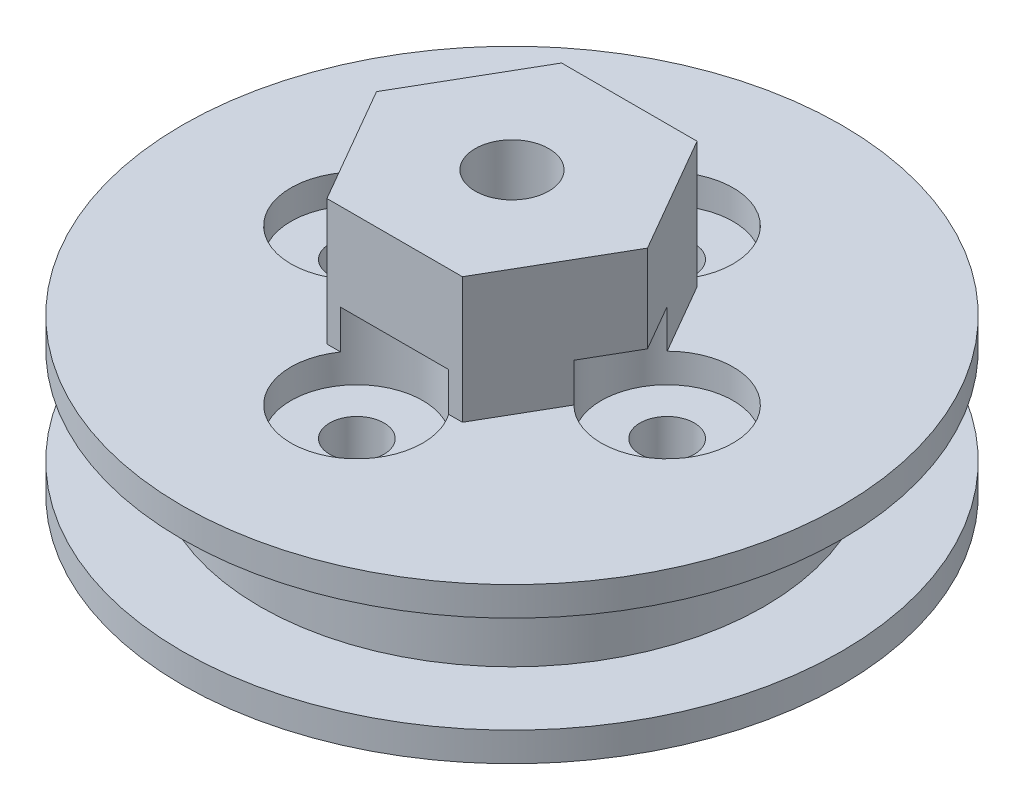
SolidWorks part; units mm, degrees
ref_plane "前视基准面" through (0, 0, 0) normal (0, 0, 1) x (1, 0, 0)
ref_plane "上视基准面" through (0, 0, 0) normal (0, 1, 0) x (1, 0, 0)
ref_plane "右视基准面" through (0, 0, 0) normal (1, 0, 0) x (0, 0, -1)
sketch "草图1" plane through (0, 0, 0) normal (0, 1, 0) x (1, 0, 0)
  circle A0 centre (0, 0) radius 17
  circle A2 centre (0, 8) radius 1.4
  circle A3 centre (8, 0) radius 1.4
  circle A4 centre (0, -8) radius 1.4
  circle A5 centre (-8, 0) radius 1.4
  circle A6 centre (0, 0) radius 4.3
  point P15 (0, 0)
  dimension "D1" = 34
  dimension "D2" = 8.6
  dimension "D3" = 2.8
  dimension "D4" = 8
  dimension "D5" = 4
extrude "凸台-拉伸1" add sketch "草图1" along normal blind 8
sketch "草图5" plane through (0, 8, 0) normal (0, 1, 0) x (1, 0, 0)
  circle A0 centre (0, -8) radius 1.4 construction
  circle A1 centre (8, 0) radius 1.4 construction
  circle A2 centre (-8, 0) radius 1.4 construction
  circle A3 centre (0, 8) radius 1.4 construction
  circle A4 centre (0, -8) radius 1.4
  circle A5 centre (8, 0) radius 1.4
  circle A6 centre (-8, 0) radius 1.4
  circle A7 centre (0, 8) radius 1.4
  circle A8 centre (0, -8) radius 3.4
  circle A9 centre (8, 0) radius 3.4
  circle A10 centre (-8, 0) radius 3.4
  circle A11 centre (0, 8) radius 3.4
  dimension "D1" = 2
extrude "切除-拉伸1" cut sketch "草图5" against normal offset from surface (1.5 mm away) 6.5 up to face at (0, 0, 17)
sketch "草图7" plane through (0, 8, 0) normal (0, 1, 0) x (1, 0, 0)
  line L0 (0, 0) -> (0, -6.05) construction
  line L1 (3.493, -6.05) -> (6.9859, 0)
  line L2 (6.9859, 0) -> (3.493, 6.05)
  line L3 (3.493, 6.05) -> (-3.493, 6.05)
  line L4 (-3.493, 6.05) -> (-6.9859, 0)
  line L5 (-6.9859, 0) -> (-3.493, -6.05)
  line L6 (-3.493, -6.05) -> (3.493, -6.05)
  circle A0 centre (0, 0) radius 6.05 construction
  circle A1 centre (0, 0) radius 1.9
  dimension "D2" = 3.8
  dimension "D1" = 12.1
extrude "凸台-拉伸5" add sketch "草图7" along normal blind 6.5
sketch "草图8" plane through (0, 8, 0) normal (0, -1, 0) x (1, 0, 0)
  line L0 (-2.7852, -6.05) -> (2.7852, -6.05) construction
  line L1 (5.5971, -2.4055) -> (6.9859, 0) construction
  line L2 (6.9859, 0) -> (5.5971, 2.4055) construction
  line L3 (-5.5971, 2.4055) -> (-6.9859, 0) construction
  line L4 (-6.9859, 0) -> (-5.5971, -2.4055) construction
  line L5 (2.7852, 6.05) -> (-2.7852, 6.05) construction
  line L6 (-2.7852, -6.05) -> (2.7852, -6.05)
  line L7 (5.5971, -2.4055) -> (6.9859, 0)
  line L8 (6.9859, 0) -> (5.5971, 2.4055)
  line L9 (-5.5971, 2.4055) -> (-6.9859, 0)
  line L10 (-6.9859, 0) -> (-5.5971, -2.4055)
  line L11 (2.7852, 6.05) -> (-2.7852, 6.05)
  arc A0 (2.7852, -6.05) -> (-2.7852, -6.05) centre (0, -8) ccw construction
  arc A1 (5.5971, 2.4055) -> (5.5971, -2.4055) centre (8, 0) ccw construction
  arc A2 (-5.5971, -2.4055) -> (-5.5971, 2.4055) centre (-8, 0) ccw construction
  arc A3 (-2.7852, 6.05) -> (2.7852, 6.05) centre (0, 8) ccw construction
  arc A4 (2.7852, -6.05) -> (-2.7852, -6.05) centre (0, -8) ccw
  arc A5 (5.5971, 2.4055) -> (5.5971, -2.4055) centre (8, 0) ccw
  arc A6 (-5.5971, -2.4055) -> (-5.5971, 2.4055) centre (-8, 0) ccw
  arc A7 (-2.7852, 6.05) -> (2.7852, 6.05) centre (0, 8) ccw
extrude "切除-拉伸2" cut sketch "草图8" against normal blind 2
sketch "草图9" plane through (0, 0, 0) normal (1, 0, 0) x (0, 0, -1)
  line L5 (-17, 8) -> (-17, 0) construction
  line L6 (-17, 6.5) -> (-13, 6.5)
  line L7 (-17, 6.5) -> (-17, 1.5)
  line L8 (-17, 1.5) -> (-13, 1.5)
  line L9 (-13, 6.5) -> (-13, 1.5)
  line L12 (-13, 4) -> (17, 4) construction
  line L13 (17, 0) -> (17, 8) construction
  line L14 (0, 18.7095) -> (0, -5.5668) construction
  dimension "D1" = 4
  dimension "D2" = 5
revolve "切除-旋转4" cut sketch "草图9" angle 360 about L14
